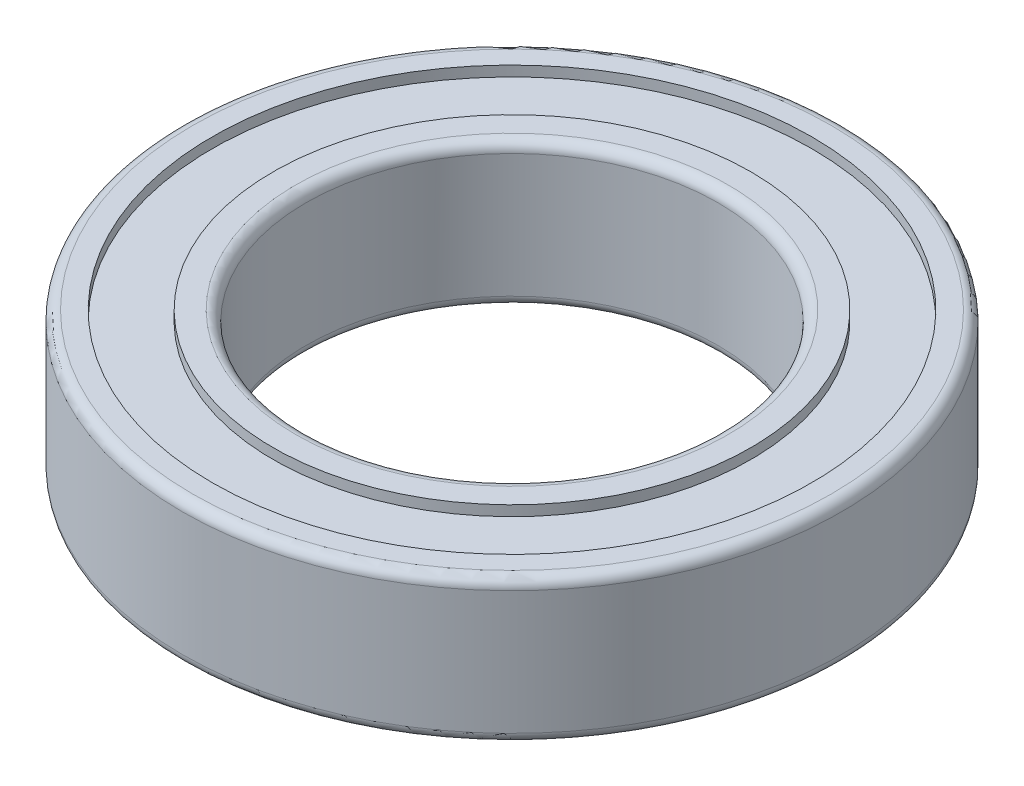
SolidWorks part; units mm, degrees
ref_plane "Ebene vorne" through (0, 0, 0) normal (0, 0, 1) x (1, 0, 0)
ref_plane "Ebene oben" through (0, 0, 0) normal (0, 1, 0) x (1, 0, 0)
ref_plane "Ebene rechts" through (0, 0, 0) normal (1, 0, 0) x (0, 0, -1)
sketch "Skizze1" plane through (0, 0, 0) normal (0, 0, 1) x (1, 0, 0)
  line L0 (0, 0) -> (0, 32.7501) construction
  line L1 (10, 0) -> (11.6, 0)
  line L2 (11.6, 0) -> (11.6, 0.5)
  line L3 (11.6, 0.5) -> (14.55, 0.5)
  line L4 (14.55, 0.5) -> (14.55, 0)
  line L5 (14.55, 0) -> (16, 0)
  line L6 (16, 0) -> (16, 7)
  line L7 (16, 7) -> (14.55, 7)
  line L8 (14.55, 7) -> (14.55, 6.5)
  line L9 (14.55, 6.5) -> (11.6, 6.5)
  line L10 (11.6, 6.5) -> (11.6, 7)
  line L11 (11.6, 7) -> (10, 7)
  line L12 (10, 7) -> (10, 0)
  point P15 (15.275, 7)
  dimension "D1" = 20
  dimension "D2" = 32
  dimension "D3" = 29.1
  dimension "D4" = 23.2
  dimension "D5" = 0.5
  dimension "D6" = 0.5
  dimension "D7" = 7
revolve "Rotation1" add sketch "Skizze1" angle 360 about L0
fillet "Verrundung1" radius 0.5 4 edges at (0, 0, -16) (0, 7, -16) (0, 0, -10) (0, 7, -10)
